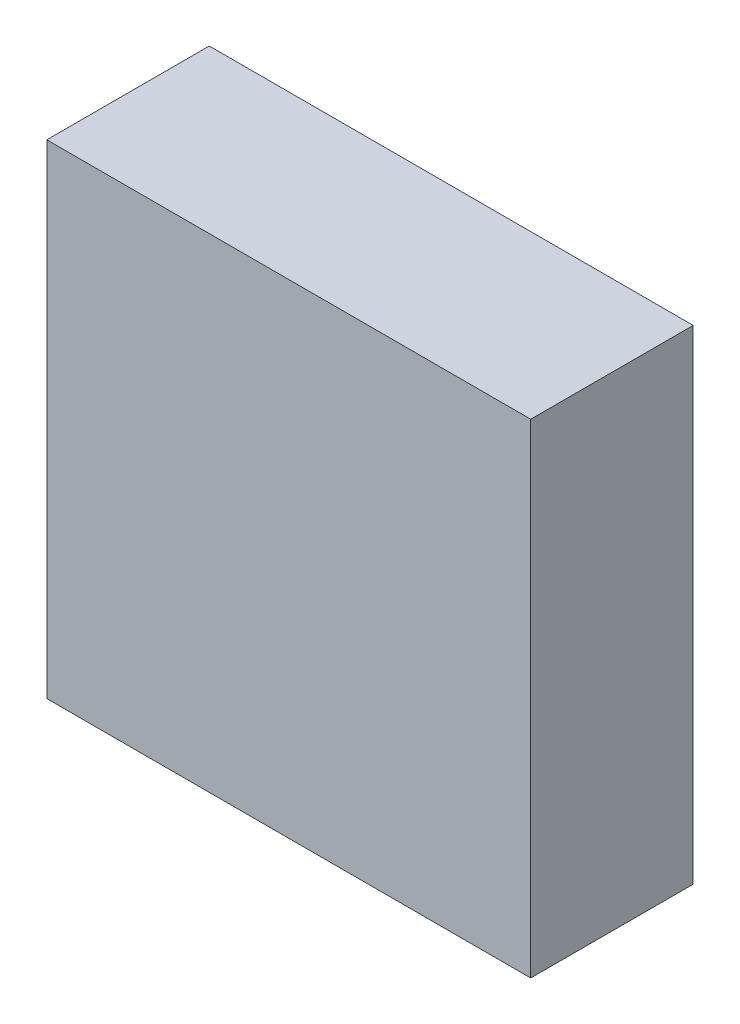
SolidWorks part; units mm, degrees
ref_plane "Front Plane" through (0, 0, 0) normal (0, 0, 1) x (1, 0, 0)
ref_plane "Top Plane" through (0, 0, 0) normal (0, 1, 0) x (1, 0, 0)
ref_plane "Right Plane" through (0, 0, 0) normal (1, 0, 0) x (0, 0, -1)
sketch "Sketch1" plane through (0, 0, 0) normal (0, 0, 1) x (1, 0, 0)
  line L1 (-4.17, -4.17) -> (4.17, -4.17)
  line L2 (-4.17, -4.17) -> (-4.17, 4.17)
  line L3 (-4.17, 4.17) -> (4.17, 4.17)
  line L4 (4.17, -4.17) -> (4.17, 4.17)
  line L5 (-4.17, -4.17) -> (4.17, 4.17) construction
  line L6 (-4.17, 4.17) -> (4.17, -4.17) construction
  point P0 (0, 0)
extrude "Envelope" add sketch "Sketch1" along normal blind 2.8
